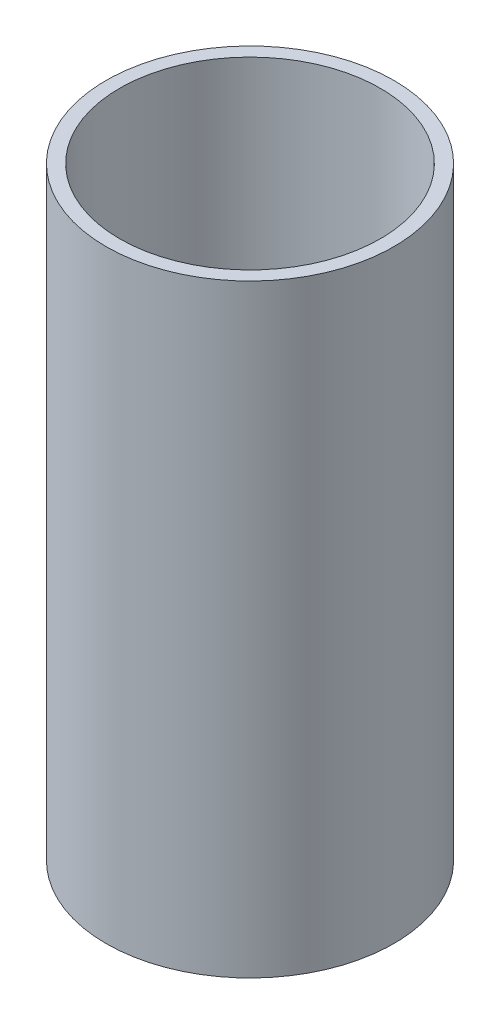
SolidWorks part; units mm, degrees
ref_plane "Front Plane" through (0, 0, 0) normal (0, 0, 1) x (1, 0, 0)
ref_plane "Top Plane" through (0, 0, 0) normal (0, 1, 0) x (1, 0, 0)
ref_plane "Right Plane" through (0, 0, 0) normal (1, 0, 0) x (0, 0, -1)
sketch "Sketch1" plane through (0, 0, 0) normal (0, 1, 0) x (1, 0, 0)
  circle A0 centre (0, 0) radius 11.925
  circle A1 centre (0, 0) radius 9.525
  dimension "D1" = 23.85
  dimension "D2" = 19.05
extrude "Boss-Extrude1" add sketch "Sketch1" along normal blind 50
sketch "Sketch2" plane through (0, 0, 0) normal (0, -1, 0) x (1, 0, 0)
  circle A0 centre (0, 0) radius 10.85
  dimension "D1" = 21.7
extrude "Cut-Extrude1" cut sketch "Sketch2" against normal blind 20
sketch "Sketch3" plane through (0, 50, 0) normal (0, 1, 0) x (1, 0, 0)
  circle A0 centre (0, 0) radius 10.8
  dimension "D1" = 21.6
extrude "Cut-Extrude2" cut sketch "Sketch3" against normal blind 20
